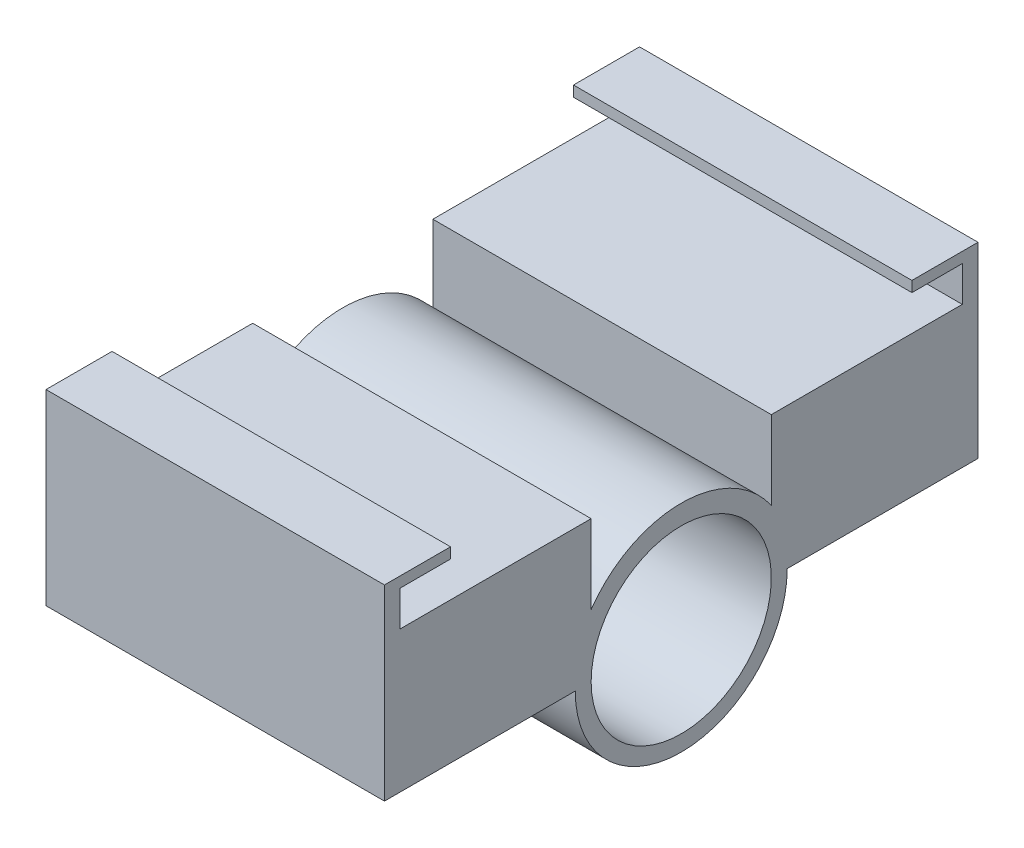
SolidWorks part; units mm, degrees
ref_plane "Front Plane" through (0, 0, 0) normal (0, 0, 1) x (1, 0, 0)
ref_plane "Top Plane" through (0, 0, 0) normal (0, 1, 0) x (1, 0, 0)
ref_plane "Right Plane" through (0, 0, 0) normal (1, 0, 0) x (0, 0, -1)
sketch "Sketch1" plane through (0, 0, 0) normal (1, 0, 0) x (0, 0, -1)
  line L2 (-15, 0) -> (-42, 0)
  line L3 (-42, 0) -> (-42, 26.5)
  line L4 (-42, 26.5) -> (-32.65, 26.5)
  line L5 (-32.65, 26.5) -> (-32.65, 25)
  line L6 (-32.65, 25) -> (-39.775, 25)
  line L7 (-39.775, 25) -> (-39.775, 20)
  line L8 (-39.775, 20) -> (-12.75, 20)
  line L9 (-12.75, 20) -> (-12.75, 8.8651)
  line L10 (0, 14.9117) -> (0, -22.1496) construction
  line L11 (12.75, 20) -> (12.75, 8.8651)
  line L12 (32.65, 26.5) -> (32.65, 25)
  line L13 (42, 26.5) -> (32.65, 26.5)
  line L14 (32.65, 25) -> (39.775, 25)
  line L15 (39.775, 25) -> (39.775, 20)
  line L16 (39.775, 20) -> (12.75, 20)
  line L17 (42, 0) -> (42, 26.5)
  line L18 (15, 0) -> (42, 0)
  arc A0 (-12.75, 0) -> (12.75, 0) centre (0, 0) ccw
  arc A1 (-15, 0) -> (15, 0) centre (0, 0) ccw
  arc A2 (-12.75, 0) -> (12.75, 0) centre (0, 0) cw
  arc A3 (-12.75, 8.8651) -> (12.75, 8.8651) centre (0, 0) cw
  dimension "D1" = 25.5
  dimension "D2" = 30
  dimension "D3" = 1.5
  dimension "D4" = 27
  dimension "D5" = 5
  dimension "D6" = 20
extrude "Boss-Extrude1" add sketch "Sketch1" along normal blind 47.9
